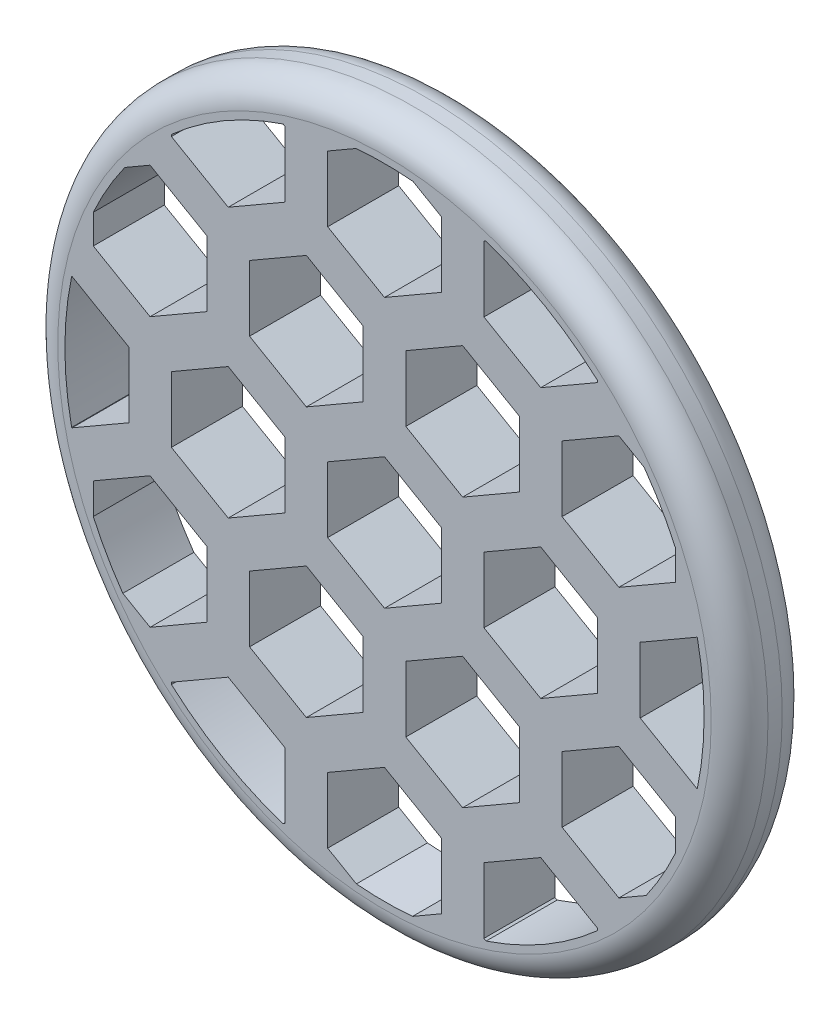
SolidWorks part; units mm, degrees
ref_plane "Front Plane" through (0, 0, 0) normal (0, 0, 1) x (1, 0, 0)
ref_plane "Top Plane" through (0, 0, 0) normal (0, 1, 0) x (1, 0, 0)
ref_plane "Right Plane" through (0, 0, 0) normal (1, 0, 0) x (0, 0, -1)
sketch "Sketch1" plane through (0, 0, 0) normal (0, 0, 1) x (1, 0, 0)
  line L0 (0, 34.4348) -> (0, -34.362) construction
  line L1 (30.2691, 0) -> (-35.0609, 0) construction
  line L2 (16.5, 4.9075) -> (20.5, 7.2169)
  line L3 (0, -4.6188) -> (4, -2.3094)
  line L4 (4, -2.3094) -> (4, 2.3094)
  line L5 (4, 2.3094) -> (0, 4.6188)
  line L6 (0, 4.6188) -> (-4, 2.3094)
  line L7 (-4, 2.3094) -> (-4, -2.3094)
  line L8 (-4, -2.3094) -> (0, -4.6188)
  line L9 (5.5, 4.9075) -> (9.5, 7.2169)
  line L10 (9.5, 7.2169) -> (9.5, 11.8357)
  line L11 (9.5, 11.8357) -> (5.5, 14.1451)
  line L12 (5.5, 14.1451) -> (1.5, 11.8357)
  line L13 (1.5, 11.8357) -> (1.5, 7.2169)
  line L14 (1.5, 7.2169) -> (5.5, 4.9075)
  line L15 (20.5, 7.2169) -> (20.5, 11.8357)
  line L16 (20.5, 11.8357) -> (16.5, 14.1451)
  line L17 (16.5, 14.1451) -> (12.5, 11.8357)
  line L18 (12.5, 11.8357) -> (12.5, 7.2169)
  line L19 (12.5, 7.2169) -> (16.5, 4.9075)
  line L20 (11, -4.6188) -> (15, -2.3094)
  line L21 (15, -2.3094) -> (15, 2.3094)
  line L22 (15, 2.3094) -> (11, 4.6188)
  line L23 (11, 4.6188) -> (7, 2.3094)
  line L24 (7, 2.3094) -> (7, -2.3094)
  line L25 (7, -2.3094) -> (11, -4.6188)
  line L32 (22, -4.6188) -> (26, -2.3094)
  line L33 (26, -2.3094) -> (26, 2.3094)
  line L34 (26, 2.3094) -> (22, 4.6188)
  line L35 (22, 4.6188) -> (18, 2.3094)
  line L36 (18, 2.3094) -> (18, -2.3094)
  line L37 (18, -2.3094) -> (22, -4.6188)
  line L38 (-11, -4.6188) -> (-7, -2.3094)
  line L39 (-7, -2.3094) -> (-7, 2.3094)
  line L40 (-7, 2.3094) -> (-11, 4.6188)
  line L41 (-11, 4.6188) -> (-15, 2.3094)
  line L42 (-15, 2.3094) -> (-15, -2.3094)
  line L43 (-15, -2.3094) -> (-11, -4.6188)
  line L44 (-5.5, 4.9075) -> (-1.5, 7.2169)
  line L45 (-1.5, 7.2169) -> (-1.5, 11.8357)
  line L46 (-1.5, 11.8357) -> (-5.5, 14.1451)
  line L47 (-5.5, 14.1451) -> (-9.5, 11.8357)
  line L48 (-9.5, 11.8357) -> (-9.5, 7.2169)
  line L49 (-9.5, 7.2169) -> (-5.5, 4.9075)
  line L50 (-22, -4.6188) -> (-18, -2.3094)
  line L51 (-18, -2.3094) -> (-18, 2.3094)
  line L52 (-18, 2.3094) -> (-22, 4.6188)
  line L53 (-22, 4.6188) -> (-26, 2.3094)
  line L54 (-26, 2.3094) -> (-26, -2.3094)
  line L55 (-26, -2.3094) -> (-22, -4.6188)
  line L56 (-16.5, 4.9075) -> (-12.5, 7.2169)
  line L57 (-12.5, 7.2169) -> (-12.5, 11.8357)
  line L58 (-12.5, 11.8357) -> (-16.5, 14.1451)
  line L59 (-16.5, 14.1451) -> (-20.5, 11.8357)
  line L60 (-20.5, 11.8357) -> (-20.5, 7.2169)
  line L61 (-20.5, 7.2169) -> (-16.5, 4.9075)
  line L68 (11, 14.3312) -> (15, 16.6406)
  line L69 (15, 16.6406) -> (15, 21.2594)
  line L70 (15, 21.2594) -> (11, 23.5688)
  line L71 (11, 23.5688) -> (7, 21.2594)
  line L72 (7, 21.2594) -> (7, 16.6406)
  line L73 (7, 16.6406) -> (11, 14.3312)
  line L74 (0, 14.3312) -> (4, 16.6406)
  line L75 (4, 16.6406) -> (4, 21.2594)
  line L76 (4, 21.2594) -> (0, 23.5688)
  line L77 (0, 23.5688) -> (-4, 21.2594)
  line L78 (-4, 21.2594) -> (-4, 16.6406)
  line L79 (-4, 16.6406) -> (0, 14.3312)
  line L80 (-11, 14.3312) -> (-7, 16.6406)
  line L81 (-7, 16.6406) -> (-7, 21.2594)
  line L82 (-7, 21.2594) -> (-11, 23.5688)
  line L83 (-11, 23.5688) -> (-15, 21.2594)
  line L84 (-15, 21.2594) -> (-15, 16.6406)
  line L85 (-15, 16.6406) -> (-11, 14.3312)
  line L92 (-5.5, -14.0285) -> (-1.5, -11.7191)
  line L93 (-1.5, -11.7191) -> (-1.5, -7.1003)
  line L94 (-1.5, -7.1003) -> (-5.5, -4.7909)
  line L95 (-5.5, -4.7909) -> (-9.5, -7.1003)
  line L96 (-9.5, -7.1003) -> (-9.5, -11.7191)
  line L97 (-9.5, -11.7191) -> (-5.5, -14.0285)
  line L98 (-16.5, -14.0285) -> (-12.5, -11.7191)
  line L99 (-12.5, -11.7191) -> (-12.5, -7.1003)
  line L100 (-12.5, -7.1003) -> (-16.5, -4.7909)
  line L101 (-16.5, -4.7909) -> (-20.5, -7.1003)
  line L102 (-20.5, -7.1003) -> (-20.5, -11.7191)
  line L103 (-20.5, -11.7191) -> (-16.5, -14.0285)
  line L104 (5.5, -14.0285) -> (9.5, -11.7191)
  line L105 (9.5, -11.7191) -> (9.5, -7.1003)
  line L106 (9.5, -7.1003) -> (5.5, -4.7909)
  line L107 (5.5, -4.7909) -> (1.5, -7.1003)
  line L108 (1.5, -7.1003) -> (1.5, -11.7191)
  line L109 (1.5, -11.7191) -> (5.5, -14.0285)
  line L110 (16.5, -14.0285) -> (20.5, -11.7191)
  line L111 (20.5, -11.7191) -> (20.5, -7.1003)
  line L112 (20.5, -7.1003) -> (16.5, -4.7909)
  line L113 (16.5, -4.7909) -> (12.5, -7.1003)
  line L114 (12.5, -7.1003) -> (12.5, -11.7191)
  line L115 (12.5, -11.7191) -> (16.5, -14.0285)
  line L128 (11, -23.5548) -> (15, -21.2454)
  line L129 (15, -21.2454) -> (15, -16.6266)
  line L130 (15, -16.6266) -> (11, -14.3172)
  line L131 (11, -14.3172) -> (7, -16.6266)
  line L132 (7, -16.6266) -> (7, -21.2454)
  line L133 (7, -21.2454) -> (11, -23.5548)
  line L134 (0, -23.5548) -> (4, -21.2454)
  line L135 (4, -21.2454) -> (4, -16.6266)
  line L136 (4, -16.6266) -> (0, -14.3172)
  line L137 (0, -14.3172) -> (-4, -16.6266)
  line L138 (-4, -16.6266) -> (-4, -21.2454)
  line L139 (-4, -21.2454) -> (0, -23.5548)
  line L140 (-11, -23.5548) -> (-7, -21.2454)
  line L141 (-7, -21.2454) -> (-7, -16.6266)
  line L142 (-7, -16.6266) -> (-11, -14.3172)
  line L143 (-11, -14.3172) -> (-15, -16.6266)
  line L144 (-15, -16.6266) -> (-15, -21.2454)
  line L145 (-15, -21.2454) -> (-11, -23.5548)
  line L152 (-22, -23.5548) -> (-18, -21.2454) [skipped]
  line L153 (-18, -21.2454) -> (-18, -16.6266) [skipped]
  line L154 (-18, -16.6266) -> (-22, -14.3172) [skipped]
  line L155 (-22, -14.3172) -> (-26, -16.6266) [skipped]
  line L156 (-26, -16.6266) -> (-26, -21.2454) [skipped]
  line L157 (-26, -21.2454) -> (-22, -23.5548) [skipped]
  line L158 (22, -23.5548) -> (26, -21.2454) [skipped]
  line L159 (26, -21.2454) -> (26, -16.6266) [skipped]
  line L160 (26, -16.6266) -> (22, -14.3172) [skipped]
  line L161 (22, -14.3172) -> (18, -16.6266) [skipped]
  line L162 (18, -16.6266) -> (18, -21.2454) [skipped]
  line L163 (18, -21.2454) -> (22, -23.5548) [skipped]
  line L170 (27.5, 4.9075) -> (31.5, 7.2169) [skipped]
  line L171 (31.5, 7.2169) -> (31.5, 11.8357) [skipped]
  line L172 (31.5, 11.8357) -> (27.5, 14.1451) [skipped]
  line L173 (27.5, 14.1451) -> (23.5, 11.8357) [skipped]
  line L174 (23.5, 11.8357) -> (23.5, 7.2169) [skipped]
  line L175 (23.5, 7.2169) -> (27.5, 4.9075) [skipped]
  line L176 (22, 14.3312) -> (26, 16.6406) [skipped]
  line L177 (26, 16.6406) -> (26, 21.2594) [skipped]
  line L178 (26, 21.2594) -> (22, 23.5688) [skipped]
  line L179 (22, 23.5688) -> (18, 21.2594) [skipped]
  line L180 (18, 21.2594) -> (18, 16.6406) [skipped]
  line L181 (18, 16.6406) -> (22, 14.3312) [skipped]
  line L182 (-22, 14.3312) -> (-18, 16.6406) [skipped]
  line L183 (-18, 16.6406) -> (-18, 21.2594) [skipped]
  line L184 (-18, 21.2594) -> (-22, 23.5688) [skipped]
  line L185 (-22, 23.5688) -> (-26, 21.2594) [skipped]
  line L186 (-26, 21.2594) -> (-26, 16.6406) [skipped]
  line L187 (-26, 16.6406) -> (-22, 14.3312) [skipped]
  circle A0 centre (0, 0) radius 25
  circle A1 centre (0, 0) radius 4 construction
  circle A2 centre (5.5, 9.5263) radius 4 construction
  circle A3 centre (0, 0) radius 22.5
  point P71 (0, 0)
  dimension "D1" = 50
  dimension "D12" = 45
  dimension "D2" = 8
  dimension "D3" = 8
  dimension "D4" = 1.5
  dimension "D5" = 3
  dimension "D6" = 16.4545
  dimension "D7" = 9.5
  dimension "D8" = 3
  dimension "D9" = 3
  dimension "D10" = 2
  dimension "D11" = 2
extrude "Boss-Extrude3" add sketch "Sketch1" along normal blind 5 contours A3 L71 A0 L82 L77 L76 | A3 L69 A0 L71 | A3 L34 A0 L69 L16 L15 | A3 L32 A0 L34 | A3 L129 A0 L32 L111 L110 | A3 L133 A0 L129 | A3 L140 A0 L133 L134 L139 | A3 L144 A0 L140 | A3 L55 A0 L144 L103 L102 | A3 L53 A0 L55 | A3 L84 A0 L53 L60 L59 | A3 L82 A0 L84 | A3 L110 L111 | A3 L139 L134 | A3 L102 L103 | A3 L59 L60 | A3 L76 L77 | A3 L15 L16 | L34 A3 L15 L2 L19 L18 L17 L16 L69 L68 L73 L72 L71 L76 L75 L74 L79 L78 L77 L82 L81 L80 L85 L84 L59 L58 L57 L56 L61 L60 L53 L52 L51 L50 L55 L102 L101 L100 L99 L98 L103 L144 L143 L142
fillet "Fillet3" radius 2 2 edges at (25, 0, 5) (25, 0, 0)
